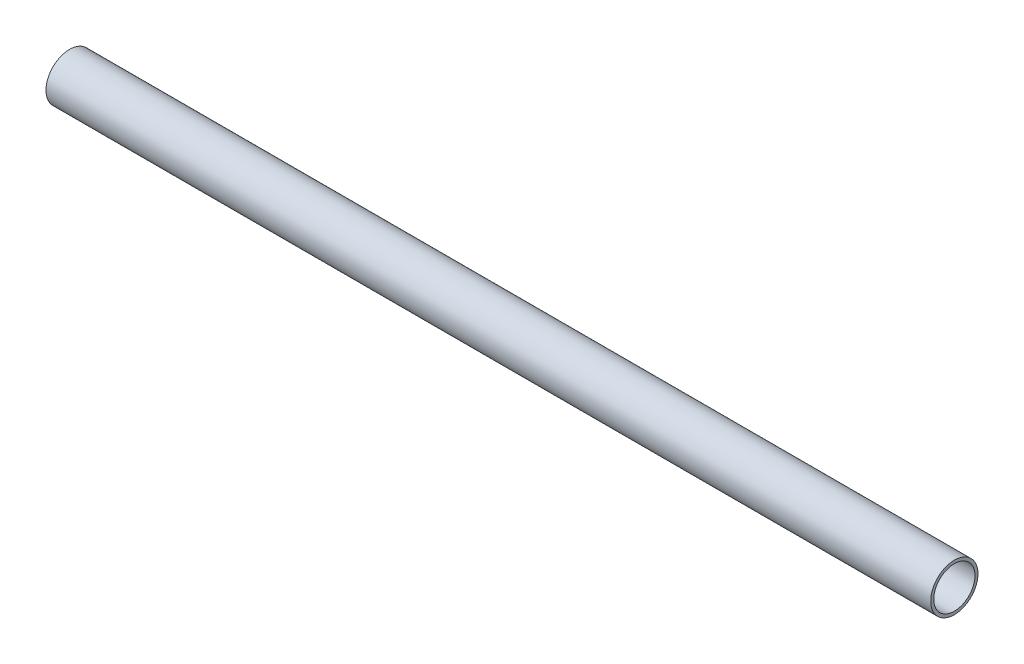
SolidWorks part; units mm, degrees
material "PVC hart"
ref_plane "Ebene vorne" through (0, 0, 0) normal (0, 0, 1) x (1, 0, 0)
ref_plane "Ebene oben" through (0, 0, 0) normal (0, 1, 0) x (1, 0, 0)
ref_plane "Ebene rechts" through (0, 0, 0) normal (1, 0, 0) x (0, 0, -1)
sketch "Skizze1" plane through (0, 0, 0) normal (1, 0, 0) x (0, 0, -1)
  circle A0 centre (0, 0) radius 7.75
  circle A1 centre (0, 0) radius 6.75
  dimension "D1" = 15.5
  dimension "D2" = 1
extrude "Aufsatz-Linear austragen1" add sketch "Skizze1" along normal blind 290
